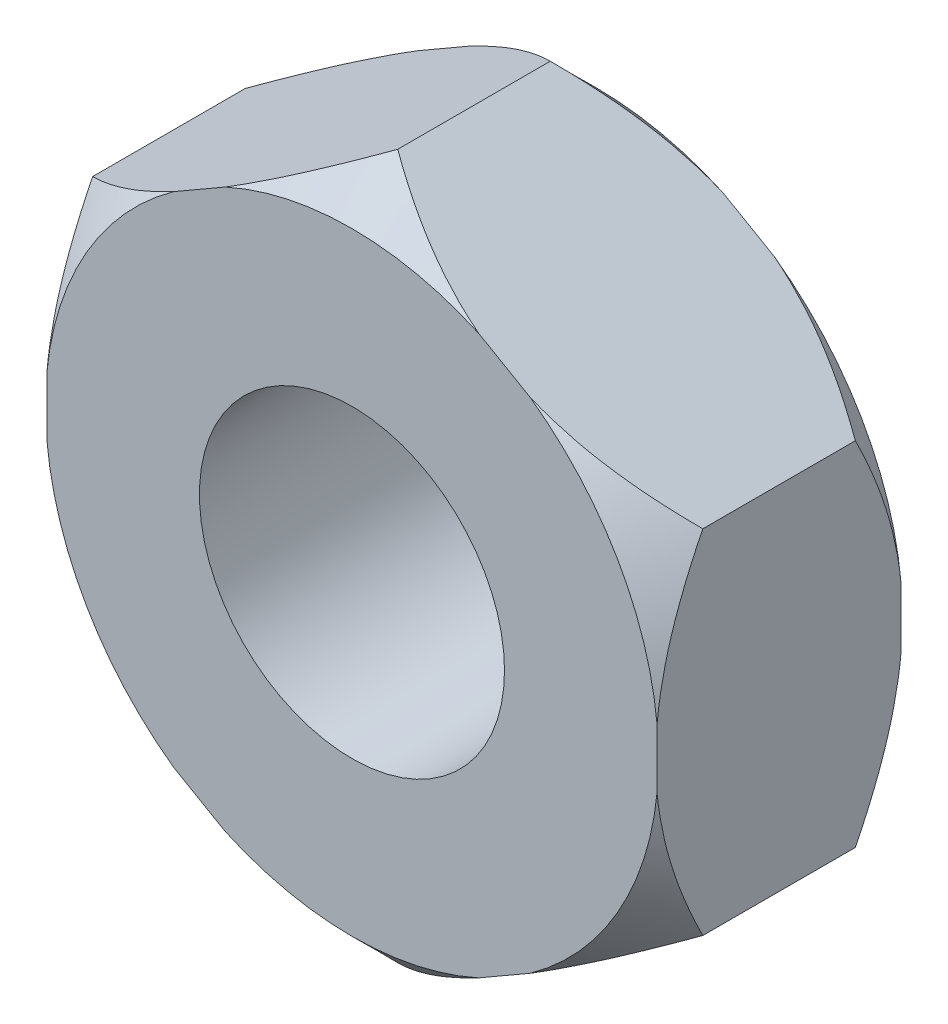
SolidWorks part; units mm, degrees
ref_plane "前视基准面" through (0, 0, 0) normal (0, 0, 1) x (1, 0, 0)
ref_plane "上视基准面" through (0, 0, 0) normal (0, 1, 0) x (1, 0, 0)
ref_plane "右视基准面" through (0, 0, 0) normal (1, 0, 0) x (0, 0, -1)
sketch "草图3" plane through (0, 0, 0) normal (0, 0, 1) x (1, 0, 0)
  line L1 (2, 1.1547) -> (0, 2.3094)
  line L2 (0, 2.3094) -> (-2, 1.1547)
  line L3 (-2, 1.1547) -> (-2, -1.1547)
  line L4 (-2, -1.1547) -> (0, -2.3094)
  line L5 (0, -2.3094) -> (2, -1.1547)
  line L6 (2, -1.1547) -> (2, 1.1547)
  circle A0 centre (0, 0) radius 2 construction
  circle A2 centre (0, 0) radius 2.3094 construction
  dimension "D2" = 4
  dimension "D1" = 4
extrude "凸台-拉伸1" add sketch "草图3" along normal blind 1.6 contours L1 L2 L3 L4 L5 L6
sketch "草图5" plane through (0, 0, 0) normal (1, 0, 0) x (0, 0, -1)
  line L0 (-0.8, 2.3094) -> (-0.8, -2.3094) construction
  line L3 (-0.3, 2.3094) -> (0, 2.3094)
  line L4 (-1.6, 2.3094) -> (0, 2.3094) construction
  line L5 (0, 2.3094) -> (0, 2.0094)
  line L6 (0, 1.1547) -> (0, 2.3094) construction
  line L7 (0, 2.0094) -> (-0.3, 2.3094)
  line L8 (-1.6, 2.0094) -> (-1.3, 2.3094)
  line L9 (-1.3, 2.3094) -> (-1.6, 2.3094)
  line L10 (-1.6, 2.3094) -> (-1.6, 2.0094)
  line L11 (0, 0) -> (-1.6, 0) construction
  dimension "D1" = 0.3
  dimension "D2" = 0.3
revolve "切除-旋转1" cut sketch "草图5" angle 360 about L11
sketch "草图6" plane through (0, 0, 1.6) normal (0, 0, 1) x (1, 0, 0)
  circle A0 centre (0, 0) radius 1
  dimension "D1" = 2
extrude "切除-拉伸1" cut sketch "草图6" against normal up to surface (1.6 mm away) up to face at (0, 0, 0)
cosmetic thread "装饰螺纹线1" parameters "D2"=2.5
